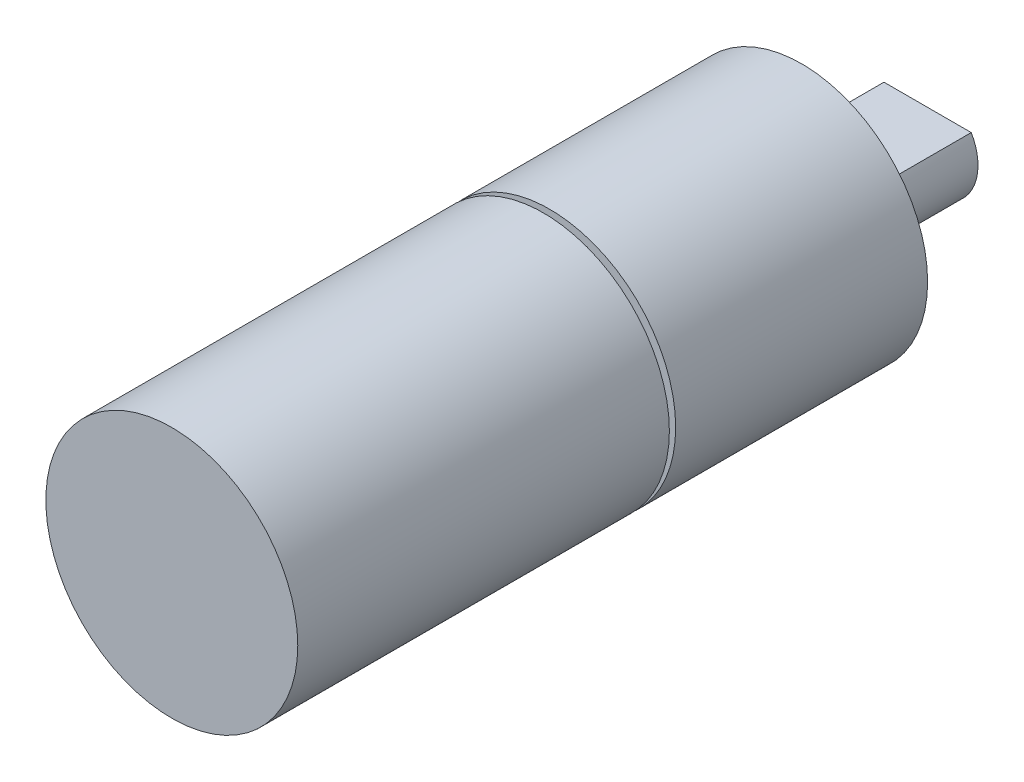
SolidWorks part; units mm, degrees
ref_plane "Front Plane" through (0, 0, 0) normal (0, 0, 1) x (1, 0, 0)
ref_plane "Top Plane" through (0, 0, 0) normal (0, 1, 0) x (1, 0, 0)
ref_plane "Right Plane" through (0, 0, 0) normal (1, 0, 0) x (0, 0, -1)
sketch "Sketch1" plane through (0, 0, 0) normal (1, 0, 0) x (0, 0, -1)
  line L0 (0, 0) -> (0, 20)
  line L1 (0, 20) -> (100, 20)
  line L2 (100, 20) -> (100, 8)
  line L3 (100, 8) -> (120, 8)
  line L4 (120, 8) -> (120, 0)
  line L5 (-24.4653, 0) -> (164.476, 0) construction
  line L6 (0, 0) -> (120, 0)
  dimension "D1" = 100
  dimension "D2" = 20
  dimension "D3" = 8
  dimension "D4" = 20
revolve "Revolve1" add sketch "Sketch1" angle 360 about L5
sketch "Sketch2" plane through (0, 0, -120) normal (0, 0, -1) x (-1, 0, 0)
  line L0 (-6.9282, 4) -> (6.9282, 4)
  circle A1 centre (0, 0) radius 8
  arc A2 (6.9282, 4) -> (-6.9282, 4) centre (0, 0) ccw
  dimension "D2" = 4
  dimension "D1" = 0
extrude "Cut-Extrude1" cut sketch "Sketch2" against normal blind 15
sketch "Sketch3" plane through (0, 0, -100) normal (0, 0, -1) x (-1, 0, 0)
  circle A0 centre (0, 0) radius 18.5
  circle A1 centre (0, 0) radius 20
  circle A3 centre (0, 0) radius 20 construction
  point P5 (0, 0)
  dimension "D1" = 1.5
extrude "Cut-Extrude2" cut sketch "Sketch3" against normal blind 1 from offset 40
